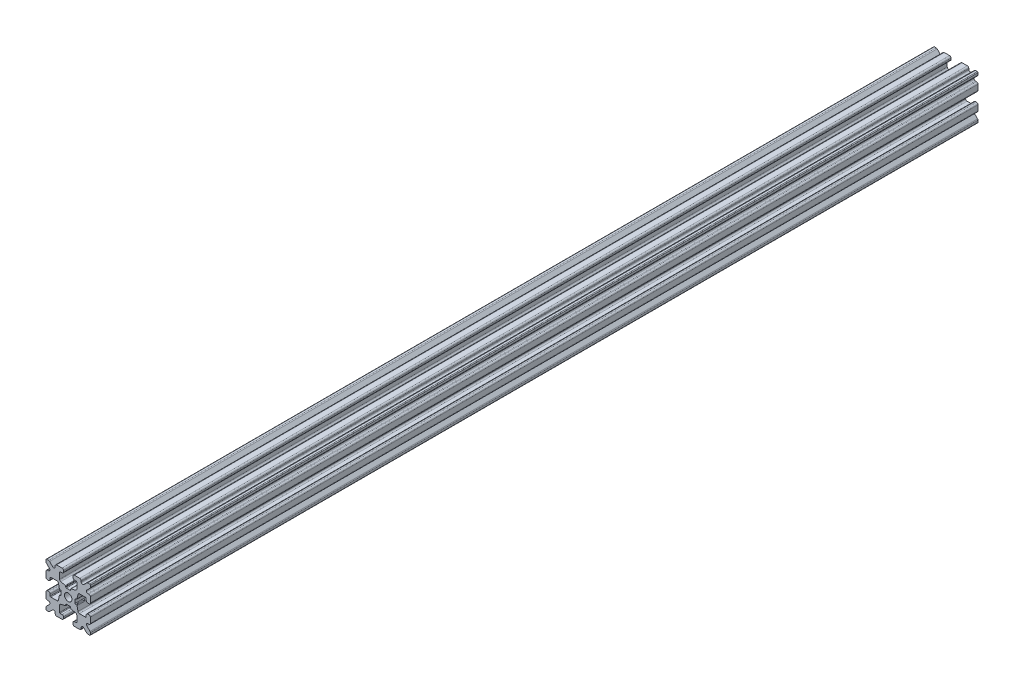
SolidWorks part; units mm, degrees
material "Alumina"
ref_plane "Front Plane" through (0, 0, 0) normal (0, 0, 1) x (1, 0, 0)
ref_plane "Top Plane" through (0, 0, 0) normal (0, 1, 0) x (1, 0, 0)
ref_plane "Right Plane" through (0, 0, 0) normal (1, 0, 0) x (0, 0, -1)
sketch "Sketch1" plane through (0, 0, 0) normal (0, 0, 1) x (1, 0, 0)
  line L1 (-7.5, -7.5) -> (7.5, -7.5)
  line L2 (-7.5, -7.5) -> (-7.5, 7.5)
  line L3 (-7.5, 7.5) -> (7.5, 7.5)
  line L4 (7.5, -7.5) -> (7.5, 7.5)
  line L5 (-7.5, -7.5) -> (7.5, 7.5) construction
  line L6 (-7.5, 7.5) -> (7.5, -7.5) construction
  circle A0 centre (0, 0) radius 1.25
  point P0 (0, 0)
  dimension "D2" = 2.5
  dimension "D1" = 15
extrude "Change length" add sketch "Sketch1" along normal mid plane 300
fillet "Fillet1" radius 0.25 4 edges at (7.5, -7.5, 0) (-7.5, -7.5, 0) (7.5, 7.5, 0) (-7.5, 7.5, 0)
sketch "Sketch2" plane through (0, 0, 150) normal (0, 0, 1) x (1, 0, 0)
  line L0 (-7.5, 7.25) -> (-7.5, -7.25) construction
  line L1 (-7.5, 1.6) -> (-6.1, 1.6)
  line L2 (-7.5, 1.6) -> (-7.5, -1.6)
  line L3 (-7.5, -1.6) -> (-6.1, -1.6)
  line L4 (-6.1, 1.6) -> (-6.1, 2.9)
  line L5 (0, 0) -> (-12.1036, 0) construction
  line L6 (-6.1, -2.9) -> (-3.4, -2.9)
  line L7 (0, 0) -> (-7.25, 7.25) construction
  line L8 (-6.1, 2.9) -> (-3.4, 2.9)
  line L9 (-3.4, -2.9) -> (-3.4, 2.9)
  line L10 (55, 0) -> (-55, 0) construction
  line L11 (-6.1, -2.9) -> (-6.1, -1.6)
  line L12 (2.9, 6.1) -> (1.6, 6.1)
  line L13 (2.9, 3.4) -> (-2.9, 3.4)
  line L14 (-2.9, 6.1) -> (-2.9, 3.4)
  line L15 (2.9, 6.1) -> (2.9, 3.4)
  line L16 (-1.6, 6.1) -> (-2.9, 6.1)
  line L17 (1.6, 7.5) -> (1.6, 6.1)
  line L18 (-1.6, 7.5) -> (1.6, 7.5)
  line L19 (-1.6, 7.5) -> (-1.6, 6.1)
  line L20 (-1.6, -7.5) -> (-1.6, -6.1)
  line L21 (-1.6, -7.5) -> (1.6, -7.5)
  line L22 (1.6, -7.5) -> (1.6, -6.1)
  line L23 (-1.6, -6.1) -> (-2.9, -6.1)
  line L24 (2.9, -6.1) -> (2.9, -3.4)
  line L25 (-2.9, -6.1) -> (-2.9, -3.4)
  line L26 (2.9, -3.4) -> (-2.9, -3.4)
  line L27 (2.9, -6.1) -> (1.6, -6.1)
  line L28 (6.1, -2.9) -> (6.1, -1.6)
  line L29 (3.4, -2.9) -> (3.4, 2.9)
  line L30 (6.1, 2.9) -> (3.4, 2.9)
  line L31 (6.1, -2.9) -> (3.4, -2.9)
  line L32 (6.1, 1.6) -> (6.1, 2.9)
  line L33 (7.5, -1.6) -> (6.1, -1.6)
  line L34 (7.5, 1.6) -> (7.5, -1.6)
  line L35 (7.5, 1.6) -> (6.1, 1.6)
  dimension "D1" = 3.2
  dimension "D2" = 5.8
  dimension "D3" = 1.4
  dimension "D4" = 2.7
extrude "Cut-Extrude1" cut sketch "Sketch2" against normal through all
sketch "Sketch4" plane through (0, 0, 150) normal (0, 0, 1) x (1, 0, 0)
  line L0 (-3.4, 2.9) -> (-2.75, 0)
  line L1 (55, 0) -> (-55, 0) construction
  line L2 (-2.75, 0) -> (-3.4, -2.9)
  line L3 (-3.4, -2.9) -> (-3.4, 2.9) construction
  line L4 (-3.4, 2.9) -> (-3.4, -2.9)
  line L5 (-2.9, 3.4) -> (0, 2.75)
  line L6 (0, 2.75) -> (2.9, 3.4)
  line L7 (2.9, 3.4) -> (-2.9, 3.4)
  line L8 (3.4, 2.9) -> (2.75, 0)
  line L9 (2.75, 0) -> (3.4, -2.9)
  line L10 (3.4, -2.9) -> (3.4, 2.9)
  line L11 (-2.9, -3.4) -> (0, -2.75)
  line L12 (0, -2.75) -> (2.9, -3.4)
  line L13 (2.9, -3.4) -> (-2.9, -3.4)
  circle A2 centre (0, 0) radius 2.75
  circle A3 centre (0, 0) radius 2.75 construction
  dimension "D1" = 1.5
extrude "Cut-Extrude3" cut sketch "Sketch4" against normal through all
fillet "Fillet3" radius 0.5 16 edges at (-6.1, -1.6, 0) (-7.5, -1.6, 0) (-6.1, 1.6, 0) (-7.5, 1.6, 0) (-1.6, -7.5, 0) (-1.6, -6.1, 0) (1.6, -7.5, 0) (1.6, -6.1, 0) (6.1, -1.6, 0) (7.5, -1.6, 0) (7.5, 1.6, 0) (6.1, 1.6, 0) (1.6, 7.5, 0) (1.6, 6.1, 0) (-1.6, 7.5, 0) (-1.6, 6.1, 0)
fillet "Fillet4" radius 0.5 8 edges at (-3.4, 2.9, 0) (-3.4, -2.9, 0) (2.9, -3.4, 0) (-2.9, -3.4, 0) (3.4, -2.9, 0) (3.4, 2.9, 0) (-2.9, 3.4, 0) (2.9, 3.4, 0)
fillet "Fillet5" radius 3 4 edges at (0, -2.75, 0) (2.75, 0, 0) (-2.75, 0, 0) (0, 2.75, 0)
fillet "Fillet6" radius 0.2 8 edges at (-2.9, -6.1, 0) (2.9, -6.1, 0) (6.1, -2.9, 0) (6.1, 2.9, 0) (2.9, 6.1, 0) (-2.9, 6.1, 0) (-6.1, -2.9, 0) (-6.1, 2.9, 0)
sketch "Sketch5" plane through (0, 0, 150) normal (0, 0, 1) x (1, 0, 0)
  line L0 (0, 0) -> (-7.25, 7.25) construction
  line L1 (-7.5, 6.4393) -> (-5.4607, 4.4)
  line L2 (-6.4393, 7.5) -> (-4.4, 5.4607)
  line L3 (-7.5, 4.4) -> (-5.4607, 4.4)
  line L4 (-3.8003, 2.9) -> (-5.9, 2.9) construction
  line L5 (0, 0) -> (-12.1819, 0) construction
  line L6 (-4.4, 7.5) -> (-4.4, 5.4607)
  line L7 (-2.9, 5.9) -> (-2.9, 3.8003) construction
  line L8 (-7.5, 6.4393) -> (-7.5, 4.4)
  line L9 (-7.5, 7.25) -> (-7.5, 2.1) construction
  line L10 (2.1, -7.5) -> (7.25, -7.5) construction
  line L11 (7.5, -7.25) -> (7.5, -2.1) construction
  line L12 (7.25, 7.5) -> (2.1, 7.5) construction
  line L13 (-2.1, 7.5) -> (-7.25, 7.5) construction
  line L14 (-4.4, 7.5) -> (-6.4393, 7.5)
  line L16 (55, 0) -> (-55, 0) construction
  line L17 (0, 0) -> (0, 10.993) construction
  line L18 (0, -54.6431) -> (0, 54.6431) construction
  line L20 (4.4, 7.5) -> (6.4393, 7.5)
  line L22 (7.5, 6.4393) -> (7.5, 4.4)
  line L23 (4.4, 7.5) -> (4.4, 5.4607)
  line L24 (7.5, 4.4) -> (5.4607, 4.4)
  line L25 (6.4393, 7.5) -> (4.4, 5.4607)
  line L26 (7.5, 6.4393) -> (5.4607, 4.4)
  line L27 (7.5, -6.4393) -> (5.4607, -4.4)
  line L28 (6.4393, -7.5) -> (4.4, -5.4607)
  line L29 (7.5, -4.4) -> (5.4607, -4.4)
  line L30 (4.4, -7.5) -> (4.4, -5.4607)
  line L31 (7.5, -6.4393) -> (7.5, -4.4)
  line L33 (4.4, -7.5) -> (6.4393, -7.5)
  line L36 (-4.4, -7.5) -> (-6.4393, -7.5)
  line L38 (-7.5, -6.4393) -> (-7.5, -4.4)
  line L39 (-4.4, -7.5) -> (-4.4, -5.4607)
  line L40 (-7.5, -4.4) -> (-5.4607, -4.4)
  line L41 (-6.4393, -7.5) -> (-4.4, -5.4607)
  line L42 (-7.5, -6.4393) -> (-5.4607, -4.4)
  dimension "D1" = 1.5
  dimension "D2" = 1.5
  dimension "D3" = 1.5
extrude "Cut-Extrude4" cut sketch "Sketch5" against normal through all
fillet "Fillet8" radius 0.5 24 edges at (-5.4607, 4.4, 0) (-7.5, 4.4, 0) (-5.4607, -4.4, 0) (-7.5, -4.4, 0) (-4.4, -7.5, 0) (-4.4, -5.4607, 0) (4.4, -7.5, 0) (4.4, -5.4607, 0) (5.4607, -4.4, 0) (7.5, -4.4, 0) (7.5, 4.4, 0) (5.4607, 4.4, 0) (4.4, 5.4607, 0) (4.4, 7.5, 0) (-4.4, 5.4607, 0) (-4.4, 7.5, 0) (-6.4393, 7.5, 0) (-7.5, 6.4393, 0) (6.4393, 7.5, 0) (7.5, 6.4393, 0) (6.4393, -7.5, 0) (7.5, -6.4393, 0) (-6.4393, -7.5, 0) (-7.5, -6.4393, 0)
sketch "Sketch6" plane through (0, 0, 150) normal (0, 0, 1) x (1, 0, 0)
  line L0 (0, 0) -> (0, 11.013) construction
  line L1 (0.6561, 2.8971) -> (2.1235, 2.8971) construction
  line L2 (0, -54.6431) -> (0, 54.6431) construction
  line L3 (0, 0) -> (7.25, 7.25) construction
  line L4 (7.5, 0.8255) -> (7.5, -0.8255)
  line L5 (2.3471, 0.8255) -> (7.5, 0.8255)
  line L6 (0, 0) -> (12.4016, 0) construction
  line L7 (0.8255, -7.5) -> (-0.8255, -7.5)
  line L8 (2.3471, -0.8255) -> (2.3471, 0.8255)
  line L9 (0.8255, -2.3471) -> (0.8255, -7.5)
  line L10 (7.5, -0.8255) -> (2.3471, -0.8255)
  line L11 (-7.5, -0.8255) -> (-2.3471, -0.8255)
  line L12 (-2.3471, -0.8255) -> (-2.3471, 0.8255)
  line L13 (-0.8255, -2.3471) -> (0.8255, -2.3471)
  line L14 (-0.8255, 7.5) -> (-0.8255, 2.3471)
  line L15 (-0.8255, 2.3471) -> (0.8255, 2.3471)
  line L16 (-0.8255, -7.5) -> (-0.8255, -2.3471)
  line L17 (0.8255, 2.3471) -> (0.8255, 7.5)
  line L18 (0.8255, 7.5) -> (-0.8255, 7.5)
  line L19 (3.9, 7.5) -> (2.1, 7.5) construction
  line L20 (-2.3471, 0.8255) -> (-7.5, 0.8255)
  line L21 (-7.5, 0.8255) -> (-7.5, -0.8255)
  point P5 (0, -2.5973)
  point P7 (0, 2.5973)
  dimension "D3" = 0.55
  dimension "D1" = 1.651
extrude "Cut-Extrude5" cut sketch "Sketch6" against normal through all
fillet "Fillet10" radius 0.2 16 edges at (-2.935, 0.8255, 0) (-2.935, -0.8255, 0) (2.935, -0.8255, 0) (2.935, 0.8255, 0) (0.8255, 2.935, 0) (-0.8255, 2.935, 0) (-2.3471, 0.8255, 0) (-2.3471, -0.8255, 0) (0.8255, 2.3471, 0) (-0.8255, 2.3471, 0) (2.3471, 0.8255, 0) (2.3471, -0.8255, 0) (0.8255, -2.935, 0) (0.8255, -2.3471, 0) (-0.8255, -2.3471, 0) (-0.8255, -2.935, 0)
